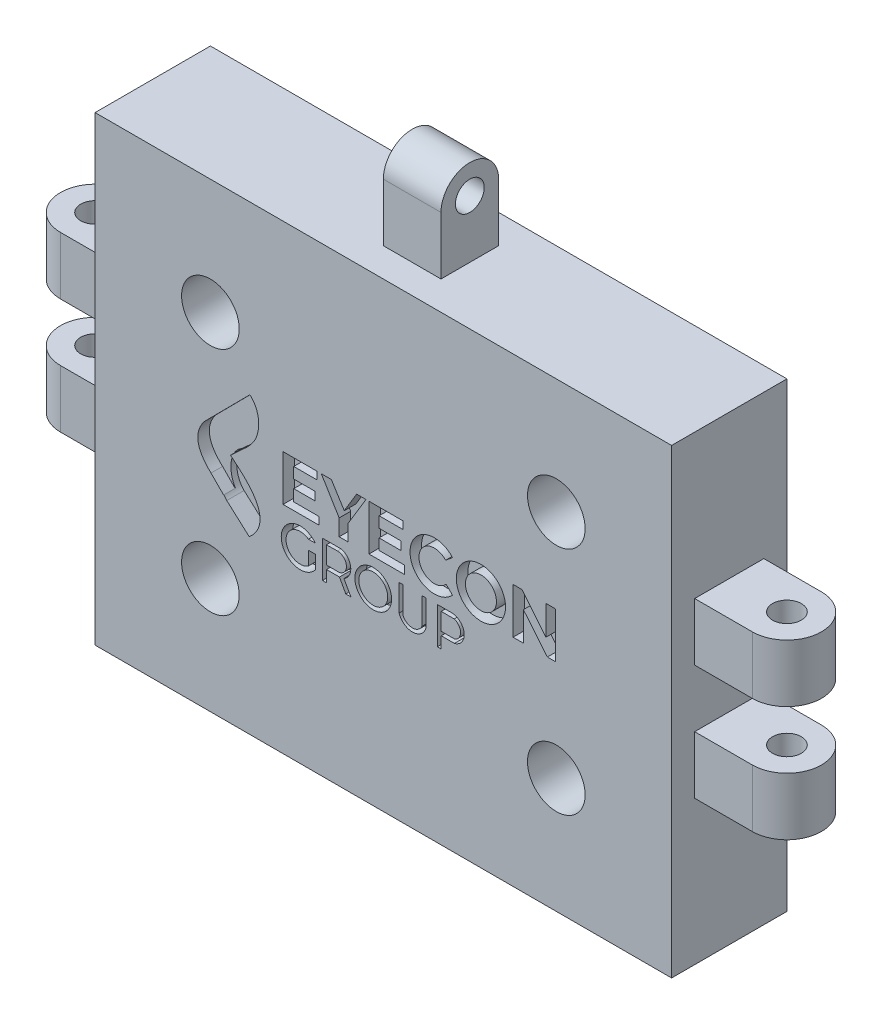
SolidWorks part; units mm, degrees
ref_plane "Front Plane" through (0, 0, 0) normal (0, 0, 1) x (1, 0, 0)
ref_plane "Top Plane" through (0, 0, 0) normal (0, 1, 0) x (1, 0, 0)
ref_plane "Right Plane" through (0, 0, 0) normal (1, 0, 0) x (0, 0, -1)
sketch "Sketch1" plane through (669.8418, 0, 0) normal (0, 0, 1) x (1, 0, 0)
  line L1 (-696.3103, 457.6379) -> (-646.3103, 457.6379)
  line L2 (-696.3103, 457.6379) -> (-696.3103, 417.6379)
  line L3 (-696.3103, 417.6379) -> (-646.3103, 417.6379)
  line L4 (-646.3103, 457.6379) -> (-646.3103, 417.6379)
  dimension "50" = 50
  dimension "D2" = 40
extrude "Boss-Extrude1" add sketch "Sketch1" along normal blind 10
sketch "Sketch5" plane through (23.5315, 0, 0) normal (1, 0, 0) x (0, 0, -1)
  line L0 (0, 417.6379) -> (0, 457.6379) construction
  line L1 (-8, 445.1379) -> (-2, 445.1379)
  line L2 (-8, 445.1379) -> (-8, 440.1379)
  line L3 (-8, 440.1379) -> (-2, 440.1379)
  line L4 (-2, 445.1379) -> (-2, 440.1379)
  line L5 (-8, 435.1379) -> (-2, 435.1379)
  line L6 (-8, 435.1379) -> (-8, 430.1379)
  line L7 (-8, 430.1379) -> (-2, 430.1379)
  line L8 (-2, 435.1379) -> (-2, 430.1379)
  line L9 (-10, 417.6379) -> (-10, 457.6379) construction
  line L10 (0, 437.6379) -> (-10, 437.6379)
  line L11 (-2, 440.1379) -> (-2, 437.6379)
  line L12 (-8, 435.1379) -> (-8, 437.6379)
  dimension "D1" = 5
  dimension "D2" = 2
  dimension "D3" = 2
  dimension "D4" = 2
  dimension "D5" = 2
  dimension "D6" = 5
  dimension "D7" = 5
extrude "Boss-Extrude3" add sketch "Sketch5" along normal blind 10 contours L4 L1 L2 L3 | L8 L5 L6 L7
sketch "Sketch6" plane through (669.8418, 445.1379, 0) normal (0, 1, 0) x (1, 0, 0)
  line L1 (-646.3103, -8) -> (-646.3103, -2) construction
  line L2 (-646.3103, -5) -> (-636.3103, -5) construction
  line L3 (-636.3103, -8) -> (-636.3103, -2) construction
  line L4 (-641.3103, -8) -> (-641.3103, -2) construction
  line L5 (-636.3103, -8) -> (-646.3103, -8) construction
  line L6 (-636.3103, -2) -> (-646.3103, -2) construction
  circle A1 centre (-641.3103, -5) radius 1.25
  dimension "D1" = 2.5
extrude "Cut-Extrude1" cut sketch "Sketch6" against normal blind 20
sketch "Sketch8" plane through (-26.4685, 0, 0) normal (-1, 0, 0) x (0, 0, 1)
  line L1 (0, 417.6379) -> (10, 417.6379)
  line L2 (0, 417.6379) -> (0, 457.6379)
  line L3 (0, 457.6379) -> (10, 457.6379)
  line L4 (10, 417.6379) -> (10, 457.6379)
extrude "Cut-Extrude2" cut sketch "Sketch8" against normal blind 25
mirror "Mirror1" about plane through (-1.4685, 0, 0) normal (1, 0, 0) of "Cut-Extrude1", "Boss-Extrude1", "Boss-Extrude3"
sketch "Sketch9" plane through (0, 435.1379, 0) normal (0, 1, 0) x (1, 0, 0)
  line L1 (23.5315, -8) -> (33.5315, -8)
  line L2 (23.5315, -8) -> (23.5315, -2)
  line L3 (23.5315, -2) -> (33.5315, -2)
  line L4 (33.5315, -8) -> (33.5315, -2)
  circle A0 centre (28.5315, -5) radius 1.9309
sketch "Sketch12" plane through (0, 457.6379, 0) normal (0, 1, 0) x (1, 0, 0)
  line L0 (23.5315, 0) -> (-26.4685, 0) construction
  line L1 (-3.9685, -2.5) -> (1.0315, -2.5)
  line L2 (-3.9685, -2.5) -> (-3.9685, -7.5)
  line L3 (-3.9685, -7.5) -> (1.0315, -7.5)
  line L4 (1.0315, -2.5) -> (1.0315, -7.5)
  line L5 (23.5315, -10) -> (-26.4685, -10) construction
  line L6 (23.5315, -10) -> (23.5315, 0) construction
  line L7 (-26.4685, -10) -> (-26.4685, 0) construction
  dimension "D1" = 2.5
  dimension "D2" = 2.5
  dimension "D3" = 22.5
  dimension "D4" = 22.5
extrude "Boss-Extrude5" add sketch "Sketch12" along normal blind 10
sketch "Sketch13" plane through (1.0315, 0, 0) normal (1, 0, 0) x (0, 0, -1)
  line L0 (-5, 467.6379) -> (-5, 457.6379) construction
  line L1 (-7.5, 467.6379) -> (-2.5, 467.6379) construction
  line L2 (-7.5, 457.6379) -> (-2.5, 457.6379) construction
  line L3 (-7.5, 462.6379) -> (-2.5, 462.6379) construction
  line L4 (-7.5, 467.6379) -> (-7.5, 457.6379) construction
  line L5 (-2.5, 467.6379) -> (-2.5, 457.6379) construction
  circle A1 centre (-5, 462.6379) radius 1.25
  dimension "D1" = 2.5
extrude "Cut-Extrude4" cut sketch "Sketch13" against normal blind 10
sketch "Sketch14" plane through (0, 0, 10) normal (0, 0, 1) x (1, 0, 0)
  line L0 (23.5315, 457.6379) -> (-26.4685, 457.6379) construction
  line L1 (23.5315, 417.6379) -> (23.5315, 457.6379) construction
  line L2 (-26.4685, 417.6379) -> (-26.4685, 457.6379) construction
  line L3 (-26.4685, 417.6379) -> (23.5315, 417.6379) construction
  circle A0 centre (-16.4685, 447.6379) radius 2.5
  circle A1 centre (-16.4685, 427.6379) radius 2.5
  circle A2 centre (13.5315, 447.6379) radius 2.5
  circle A3 centre (13.5315, 427.6379) radius 2.5
  dimension "D1" = 5
  dimension "D4" = 10
  dimension "D2" = 10
  dimension "D3" = 10
  dimension "D5" = 10
extrude "Cut-Extrude5" cut sketch "Sketch14" against normal blind 10
sketch "Sketch15" plane through (0, 445.1379, 0) normal (0, 1, 0) x (1, 0, 0)
  line L0 (28.5315, -2) -> (33.5315, -2)
  line L1 (28.5315, -8) -> (33.5315, -8)
  circle A0 centre (28.5315, -5) radius 3
  line M3 (23.5315, -8) -> (33.5315, -8)
  line M4 (33.5315, -8) -> (33.5315, -2)
  line M5 (33.5315, -2) -> (23.5315, -2)
extrude "Cut-Extrude6" cut sketch "Sketch15" against normal blind 22 contours A0 M3 M4 M5
sketch "Sketch17" plane through (0, 445.1379, 0) normal (0, 1, 0) x (1, 0, 0)
  line L0 (-31.4685, -8) -> (-36.4685, -8)
  line L1 (-36.4685, -8) -> (-36.4685, -2)
  line L2 (-36.4685, -2) -> (-31.4685, -2)
  circle A0 centre (-31.4685, -5) radius 3
  line M3 (-26.4685, -2) -> (-36.4685, -2)
  line M4 (-36.4685, -2) -> (-36.4685, -8)
  line M5 (-36.4685, -8) -> (-26.4685, -8)
extrude "Cut-Extrude7" cut sketch "Sketch17" against normal blind 30 contours A0 M3 M4 M5
sketch "Sketch18" plane through (1.0315, 0, 0) normal (1, 0, 0) x (0, 0, -1)
  line L0 (-7.5, 462.6379) -> (-7.5, 467.6379)
  line L1 (-7.5, 467.6379) -> (-2.5, 467.6379)
  line L2 (-2.5, 467.6379) -> (-2.5, 462.6379)
  circle A0 centre (-5, 462.6379) radius 2.5
  line M4 (-2.5, 457.6379) -> (-2.5, 467.6379)
  line M5 (-2.5, 467.6379) -> (-7.5, 467.6379)
  line M6 (-7.5, 467.6379) -> (-7.5, 457.6379)
extrude "Cut-Extrude8" cut sketch "Sketch18" against normal blind 30 contours A0 M4 M5 M6
scale "Scale1" bodies to scale 115 scale about centroid uniform scaling yes scale factor 2
sketch "Sketch21" plane through (0, 0, 15) normal (0, 0, 1) x (1, 0, 0)
  line L0 (18.8126, 475.8872) -> (205.4793, 475.8872) construction
  line L1 (-29.1773, 431.1695) -> (-29.0524, 431.2931)
  spline S0 degree 3 poles (-24.6101, 448.5133) (-22.7913, 446.8523) (-22.6202, 441.2009) (-27.229, 438.8768) (-28.6138, 436.9732) knots 0 0 0 0 0.4899 1 1 1 1
  spline S1 degree 1 poles (-24.6101, 448.5133) (-32.5546, 440.4957) knots 0 0 1 1
  spline S2 degree 2 poles (-32.5546, 440.4957) (-35.2442, 436.9732) (-31.3592, 433.3742) knots 0 0 0 1 1 1
  spline S3 degree 2 poles (-28.6138, 436.9732) (-31.0942, 434.2016) (-28.6221, 430.6086) knots 0 0 0 1 1 1
  spline S4 degree 1 poles (-31.3592, 433.3742) (-28.6221, 430.6086) knots 0 0 1 1
  point P10 (0, 0)
extrude "Cut-Extrude31" cut sketch "Sketch21" against normal blind 2 contours S2 S4 L1 S3 S0 S1
sketch "Sketch35" plane through (0, 0, 11) normal (0, 0, 1) x (1, 0, 0)
  line L0 (-126.2881, 445.9594) -> (60.3785, 445.9594) construction
  spline S0 degree 3 poles (-164.3118, 418.7909) (-162.3151, 417.2116) (-162.1926, 411.5555) (-166.7795, 409.2413) (-168.1651, 407.3375) knots 0 0 0 0 0.489151 1 1 1 1
  spline S1 degree 1 poles (-164.3118, 418.7909) (-172.2563, 410.7734) knots 0 0 1 1
  spline S2 degree 2 poles (-172.2563, 410.7734) (-174.6582, 407.2244) (-170.9105, 403.7385) knots 0 0 0 1 1 1
  spline S3 degree 2 poles (-168.1651, 407.3375) (-170.6455, 404.5658) (-168.1734, 400.9728) knots 0 0 0 1 1 1
  spline S4 degree 1 poles (-170.9105, 403.7385) (-168.1734, 400.9728) knots 0 0 1 1
  point P10 (-168.1651, 407.3375)
  point P13 (-167.9472, 400.9907)
  point P14 (-168.1734, 400.9728)
sketch "Sketch24" plane through (0, 0, 15) normal (0, 0, 1) x (1, 0, 0)
  line L0 (-18.8573, 442.8388) -> (-18.8573, 434.9077)
  line L1 (-18.8573, 434.9077) -> (-12.6283, 434.9077)
  line L2 (-12.6283, 434.9077) -> (-12.6283, 436.2114)
  line L3 (-17.0103, 438.2033) -> (-17.0103, 436.2114)
  line L4 (-17.0103, 436.2114) -> (-12.6283, 436.2114)
  line L5 (-13.2983, 439.6519) -> (-13.2983, 438.2033)
  line L6 (-13.2983, 438.2033) -> (-17.0103, 438.2033)
  line L7 (-13.2983, 439.6519) -> (-17.0103, 439.6519)
  line L8 (-17.0103, 439.6519) -> (-17.0103, 441.5351)
  line L9 (-17.0103, 441.5351) -> (-12.9361, 441.5351)
  line L10 (-12.9361, 441.5351) -> (-12.9361, 442.8388)
  line L11 (-12.9361, 442.8388) -> (-18.8573, 442.8388)
  line L12 (-12.2299, 442.8388) -> (-10.4916, 442.8388)
  line L13 (-10.4916, 442.8388) -> (-8.2463, 439.2716)
  line L14 (-8.2463, 439.2716) -> (-8.2463, 439.2535)
  line L15 (-8.2463, 439.2716) -> (-6.0915, 442.8388)
  line L16 (-6.0915, 442.8388) -> (-4.4799, 442.8388)
  line L17 (-4.4799, 442.8388) -> (-7.5611, 437.738)
  line L18 (-7.5611, 437.738) -> (-7.5611, 434.9077)
  line L19 (-7.5611, 434.9077) -> (-9.1335, 434.9077)
  line L20 (-9.1335, 434.9077) -> (-9.1335, 437.738)
  line L21 (-9.1335, 437.738) -> (-12.2299, 442.8388)
  line L22 (-3.9625, 442.8388) -> (-3.9625, 434.9077)
  line L23 (-3.9625, 434.9077) -> (2.2268, 434.9077)
  line L24 (2.2268, 434.9077) -> (2.2268, 436.3228)
  line L25 (2.2268, 436.3228) -> (-2.2073, 436.3228)
  line L26 (-2.2073, 436.3228) -> (-2.2073, 438.2033)
  line L27 (-2.2073, 438.2033) -> (1.5825, 438.2033)
  line L28 (1.5825, 438.2033) -> (1.5825, 439.6519)
  line L29 (1.5825, 439.6519) -> (-2.2073, 439.6519)
  line L30 (-2.2073, 439.6519) -> (-2.2073, 441.5351)
  line L31 (-2.2073, 441.5351) -> (1.9805, 441.5351)
  line L32 (1.9805, 441.5351) -> (1.9805, 442.8388)
  line L33 (1.9805, 442.8388) -> (-3.9625, 442.8388)
  line L34 (21.0337, 442.8388) -> (22.5774, 442.8388)
  line L35 (9.3336, 440.6199) -> (10.5276, 441.6161)
  line L36 (9.3336, 437.1543) -> (10.5186, 435.9692)
  line L37 (22.5774, 442.8388) -> (26.7107, 437.738)
  line L38 (28.4039, 442.8388) -> (26.7107, 442.8388)
  line L39 (26.7107, 442.8388) -> (26.7107, 437.5832)
  line L40 (28.4039, 442.8388) -> (28.4039, 434.9077)
  line L41 (28.4039, 434.9077) -> (26.9846, 434.9077)
  line L42 (26.9846, 434.9077) -> (22.8264, 439.9486)
  line L43 (22.8264, 439.9486) -> (22.8264, 434.9077)
  line L44 (22.8264, 434.9077) -> (21.0337, 434.9077)
  line L45 (21.0337, 434.9077) -> (21.0337, 442.8388)
  circle A0 centre (15.4588, 438.7976) radius 2.6901
  circle A1 centre (15.4588, 438.7976) radius 4.2668
  arc A4 (10.5276, 441.6161) -> (10.5186, 435.9692) centre (7.3794, 438.7976) ccw
  arc A5 (9.3336, 440.6199) -> (9.4178, 437.0701) centre (7.3794, 438.7976) ccw
  point P41 (0, 0)
  point P51 (0, 0)
  point P58 (0, 0)
  dimension "D5" = 8.0795
  dimension "D1" = 0.7062
  dimension "D2" = 4.4001
  dimension "D3" = 0.5174
  dimension "D4" = 5.7969
  dimension "D6" = 5.5748
  dimension "D7" = 5.5774
  dimension "D8" = 4.1333
sketch "Sketch25" plane through (0, 0, 15) normal (0, 0, 1) x (1, 0, 0)
  line L0 (-13.2769, 427.8586) -> (-13.2769, 430.2296)
  line L1 (-14.464, 430.2296) -> (-13.2769, 430.2296)
  line L2 (-14.464, 430.2296) -> (-14.464, 427.8586)
  line L3 (-14.464, 431.8902) -> (-13.2769, 431.8902)
  line L4 (-12.0208, 433.258) -> (-12.0208, 426.897)
  line L5 (-12.0208, 426.897) -> (-11.3364, 426.897)
  line L6 (-11.3364, 426.897) -> (-11.3364, 428.8915)
  line L7 (-11.3364, 428.8915) -> (-9.0823, 428.8915)
  line L8 (-9.0823, 428.8915) -> (-7.9848, 426.897)
  line L9 (-7.0997, 426.897) -> (-8.3978, 429.2219)
  line L10 (-11.3364, 432.6089) -> (-11.3364, 429.5651)
  line L11 (-12.0208, 433.258) -> (-8.6791, 433.258)
  line L12 (-9.4192, 432.6292) -> (-11.3364, 432.6089)
  line L13 (-11.3364, 429.5651) -> (-9.078, 429.5651)
  line L14 (-7.9848, 426.897) -> (-7.0997, 426.897)
  line L15 (1.2652, 433.258) -> (1.9276, 433.258)
  line L16 (1.9276, 433.258) -> (1.9276, 428.6518)
  line L17 (1.2652, 433.258) -> (1.2652, 428.6518)
  line L18 (5.2394, 428.6518) -> (5.2394, 433.258)
  line L19 (5.2394, 433.258) -> (5.887, 433.258)
  line L20 (5.887, 433.258) -> (5.887, 428.6074)
  line L21 (7.8938, 433.258) -> (7.8938, 426.897)
  line L22 (7.8938, 426.897) -> (8.5709, 426.897)
  line L23 (8.5709, 426.897) -> (8.5709, 428.8915)
  line L24 (7.8938, 433.258) -> (10.3402, 433.258)
  line L25 (8.5709, 429.5642) -> (10.913, 429.5642)
  line L26 (8.5709, 429.5642) -> (8.5709, 432.5524)
  line L27 (8.5709, 432.5524) -> (10.8215, 432.5524)
  line L28 (8.5709, 428.8915) -> (10.8615, 428.8885)
  arc A2 (-14.464, 431.8902) -> (-13.4438, 430.2296) centre (-15.8837, 429.8744) ccw
  arc A3 (-13.2769, 431.8902) -> (-13.2769, 427.8586) centre (-15.8837, 429.8744) ccw
  arc A5 (-8.6791, 433.258) -> (-8.3084, 429.0618) centre (-9.4192, 431.0782) cw
  arc A6 (-9.078, 429.5651) -> (-9.4192, 432.6292) centre (-9.4192, 431.0782) ccw
  circle A7 centre (-3.2199, 430.0756) radius 2.5054
  circle A8 centre (-3.2199, 430.0756) radius 3.1824
  arc A9 (1.9276, 428.6518) -> (5.2394, 428.6518) centre (3.5835, 429.3944) ccw
  arc A10 (1.2652, 428.6518) -> (5.887, 428.6074) centre (3.5835, 429.3944) ccw
  arc A11 (10.8215, 432.5524) -> (10.913, 429.5642) centre (10.3402, 431.0422) cw
  arc A12 (10.3402, 433.258) -> (10.8615, 428.8885) centre (10.3402, 431.0422) cw
  point P23 (0, 0)
  point P46 (0, 0)
sketch "Sketch37" plane through (0, 0, 15) normal (0, 0, 1) x (1, 0, 0)
  line L0 (-28.6221, 430.6086) -> (-24.7235, 427.1158)
  spline S0 degree 3 poles (-27.9827, 437.7334) (-25.1135, 435.4434) (-20.118, 431.2113) (-24.7235, 427.1158) knots 0 0 0 0 1 1 1 1
  spline S1 degree 3 poles (-24.6101, 448.5133) (-22.7913, 446.8523) (-22.6202, 441.2009) (-27.229, 438.8768) (-28.6138, 436.9732) knots 0 0 0 0 0.4899 1 1 1 1 construction
  spline S2 degree 3 poles (-27.9827, 437.7334) (-30.3641, 436.5057) (-30.4917, 432.4737) (-28.6221, 430.6086) knots 0 0 0 0 1 1 1 1
extrude "Cut-Extrude32" cut sketch "Sketch24" against normal blind 2
extrude "Cut-Extrude33" cut sketch "Sketch25" against normal blind 2
extrude "Cut-Extrude34" cut sketch "Sketch37" against normal blind 3
